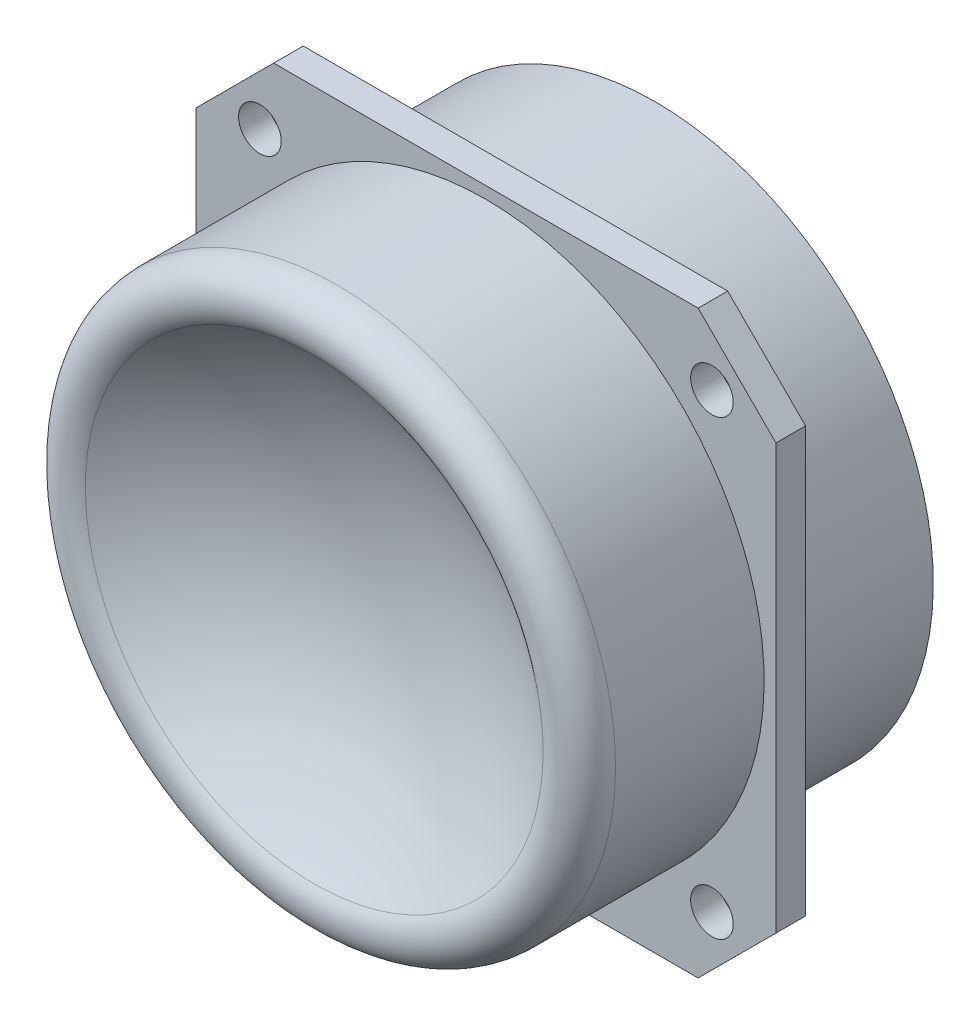
SolidWorks part; units mm, degrees
ref_plane "Front Plane" through (0, 0, 0) normal (0, 0, 1) x (1, 0, 0)
ref_plane "Top Plane" through (0, 0, 0) normal (0, 1, 0) x (1, 0, 0)
ref_plane "Right Plane" through (0, 0, 0) normal (1, 0, 0) x (0, 0, -1)
sketch "Sketch1" plane through (0, 0, 0) normal (0, 0, 1) x (1, 0, 0)
  line L1 (-24.5, -24.5) -> (24.5, -24.5)
  line L2 (-24.5, -24.5) -> (-24.5, 24.5)
  line L3 (-24.5, 24.5) -> (24.5, 24.5)
  line L4 (24.5, -24.5) -> (24.5, 24.5)
  line L5 (0, 24.5) -> (0, -24.5) construction
  line L6 (-24.5, 0) -> (24.5, 0) construction
  point P0 (0, 0)
  dimension "D1" = 49
extrude "Boss-Extrude1" add sketch "Sketch1" against normal blind 2.5
sketch "Sketch2" plane through (0, 0, 0) normal (1, 0, 0) x (0, 0, -1)
  line L0 (0, 0) -> (-14.5013, 0) construction
  line L1 (2.5, 0) -> (14.29, 0) construction
  line L2 (2.5, -24.5) -> (2.5, 24.5) construction
  line L3 (14.29, 0) -> (14.29, 23.5)
  line L4 (14.29, 23.5) -> (-12.55, 23.5)
  line L5 (14.29, 0) -> (-7.5013, 0)
  line L6 (0, -24.5) -> (0, 24.5) construction
  arc A0 (-14.5013, 19.3339) -> (-7.5013, 0) centre (-37.7012, 0) cw
  arc A1 (-12.55, 23.5) -> (-14.5013, 19.3339) centre (-12.55, 20.96) ccw
  point P1 (0, 0)
  point P10 (-8.8067, -16.4474)
  point P17 (-15.09, 18.3299)
  point P18 (-14.7515, 20.96)
  point P19 (0, 0)
  point P20 (-10.2059, -17.5229)
  point P21 (0, 0)
  point P22 (-7.2506, 1.5701)
  point P23 (14.0809, 0)
  dimension "D1" = 7
  dimension "D4" = 2.54
  dimension "D3" = 29.38
  dimension "D2" = 47
  dimension "D5" = 12.55
revolve "Revolve1" add sketch "Sketch2" angle 360 about L0
sketch "Sketch3" plane through (0, 0, 0) normal (0, 0, 1) x (1, 0, 0)
  line L0 (-24.5, 17.9264) -> (-17.9264, 24.5)
  line L1 (-24.5, 24.5) -> (-24.5, -24.5) construction
  line L2 (24.5, 24.5) -> (-24.5, 24.5) construction
  line L3 (24.5, 17.9264) -> (17.9264, 24.5)
  line L4 (-24.5, -17.9264) -> (-24.5, -24.5)
  line L5 (24.5, -17.9264) -> (17.9264, -24.5)
  line L6 (24.5, -24.5) -> (24.5, 24.5) construction
  line L7 (-24.5, -24.5) -> (24.5, -24.5) construction
  line L8 (-24.5, -17.9264) -> (-17.9264, -24.5)
  line L9 (21.2132, 21.2132) -> (-21.2132, -21.2132) construction
  line L10 (21.2132, -21.2132) -> (-21.2132, 21.2132) construction
  line L11 (-17.9264, 24.5) -> (-24.5, 24.5)
  line L12 (24.5, 17.9264) -> (24.5, 24.5)
  line L13 (17.9264, -24.5) -> (24.5, -24.5)
  line L14 (24.5, -24.5) -> (24.5, 24.5)
  line L15 (24.5, 24.5) -> (-24.5, 24.5)
  line L16 (-24.5, 24.5) -> (-24.5, -24.5)
  line L17 (-24.5, -24.5) -> (24.5, -24.5)
  line L18 (24.5, -24.5) -> (24.5, -17.9264)
  line L19 (24.5, 24.5) -> (17.9264, 24.5)
  line L20 (-24.5, 24.5) -> (-24.5, 17.9264)
  line L21 (-24.5, -24.5) -> (-17.9264, -24.5)
  point P16 (0, 0)
  point P19 (20.4902, -20.4902)
  point P20 (0, 0)
  point P24 (0, 0)
  point P25 (20.262, 20.262)
  point P26 (20.1931, -20.1931)
  point P27 (24.5, -16.013)
  point P28 (0, 0)
  point P29 (-20.1876, 20.1876)
  dimension "D1" = 60
  dimension "D2" = 0
extrude "Cut-Extrude1" cut sketch "Sketch3" against normal blind 2.5
hole_wizard "Ø3.6 (3.6) Diameter Hole1" positions "Sketch4" profile "Sketch5" hole size "Ø3.6" standard "ANSI Metric" end condition through all
sketch "Sketch4" plane through (0, 0, 0) normal (0, 0, 1) x (1, 0, 0)
  line L0 (-19.0919, 19.0919) -> (19.0919, -19.0919) construction
  line L3 (-19.0919, -19.0919) -> (19.0919, 19.0919) construction
  line L5 (-17.9264, -24.5) -> (-24.5, -17.9264) construction
  point P1 (-19.0919, 19.0919)
  point P2 (19.0919, -19.0919)
  point P5 (-19.0919, -19.0919)
  point P6 (19.0919, 19.0919)
  dimension "D1" = 54
sketch "Sketch5" plane through (-19.0919, 19.0919, 0) normal (1, 0, 0) x (0, -1, 0)
  line L0 (0, 0) -> (0, 14.29)
  line L1 (0, 14.29) -> (1.8, 14.29)
  line L2 (1.8, 14.29) -> (1.8, 0)
  line L5 (1.8, 0) -> (0, 0)
  line L11 (0, -6.35) -> (0, 107.95) construction
  dimension "Thru Hole Dia." = 3.6
  dimension "Thru Hole Depth" = 14.29
